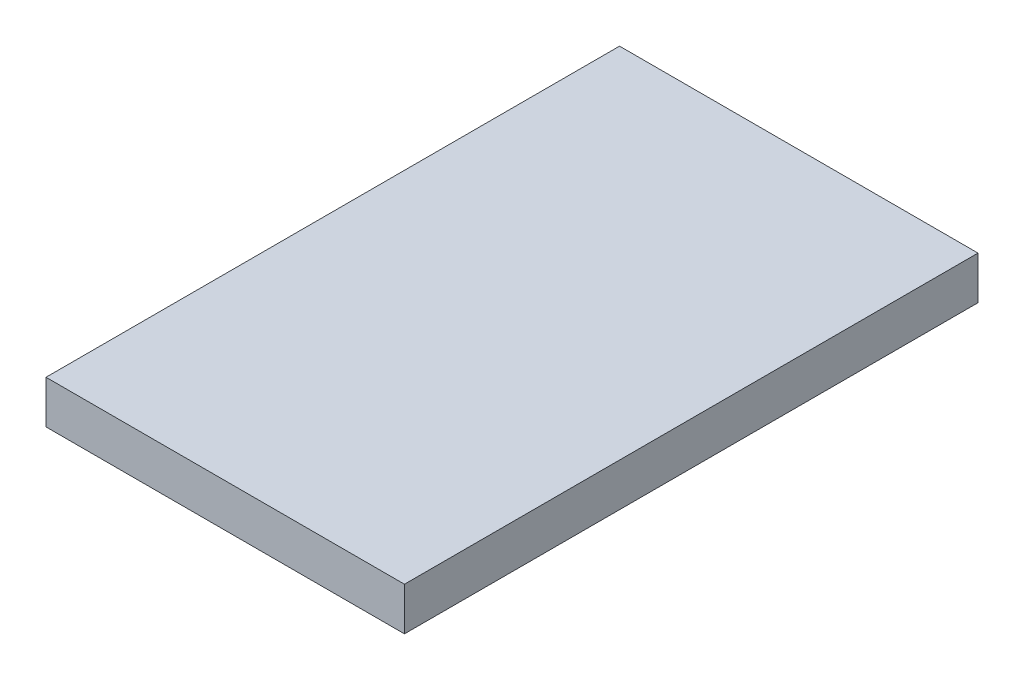
SolidWorks part; units mm, degrees
ref_plane "Front Plane" through (0, 0, 0) normal (0, 0, 1) x (1, 0, 0)
ref_plane "Top Plane" through (0, 0, 0) normal (0, 1, 0) x (1, 0, 0)
ref_plane "Right Plane" through (0, 0, 0) normal (1, 0, 0) x (0, 0, -1)
sketch "Sketch1" plane through (0, 0, 0) normal (0, 1, 0) x (1, 0, 0)
  line L1 (-12.5, 20) -> (12.5, 20)
  line L2 (-12.5, 20) -> (-12.5, -20)
  line L3 (-12.5, -20) -> (12.5, -20)
  line L4 (12.5, 20) -> (12.5, -20)
  line L5 (-12.5, 20) -> (12.5, -20) construction
  line L6 (-12.5, -20) -> (12.5, 20) construction
  point P0 (0, 0)
  dimension "D1" = 40
  dimension "D2" = 25
extrude "Boss-Extrude1" add sketch "Sketch1" along normal blind 3
